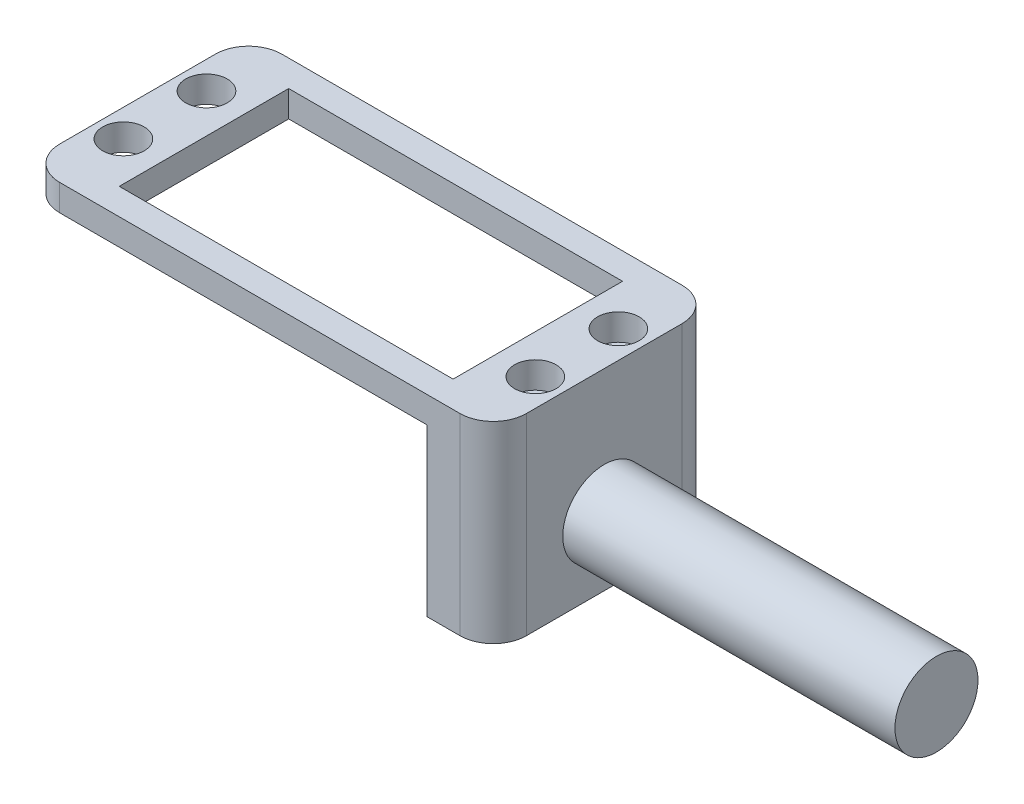
SolidWorks part; units mm, degrees
ref_plane "Front Plane" through (0, 0, 0) normal (0, 0, 1) x (1, 0, 0)
ref_plane "Top Plane" through (0, 0, 0) normal (0, 1, 0) x (1, 0, 0)
ref_plane "Right Plane" through (0, 0, 0) normal (1, 0, 0) x (0, 0, -1)
sketch "Sketch1" plane through (0, 0, 0) normal (0, 1, 0) x (1, 0, 0)
  line L0 (0, 13.375) -> (0, -13.375) construction
  line L1 (-20.1, 10.2) -> (20.1, 10.2)
  line L2 (-20.1, 10.2) -> (-20.1, -10.2)
  line L3 (-20.1, -10.2) -> (20.1, -10.2)
  line L4 (20.1, 10.2) -> (20.1, -10.2)
  line L5 (-20.1, 10.2) -> (20.1, -10.2) construction
  line L6 (-20.1, -10.2) -> (20.1, 10.2) construction
  line L7 (-28.1, 13.375) -> (28.1, 13.375)
  line L8 (-28.1, 13.375) -> (-28.1, -13.375)
  line L9 (-28.1, -13.375) -> (28.1, -13.375)
  line L10 (28.1, 13.375) -> (28.1, -13.375)
  line L11 (-28.1, 13.375) -> (28.1, -13.375) construction
  line L12 (-28.1, -13.375) -> (28.1, 13.375) construction
  circle A0 centre (24.8, 5) radius 2.5
  circle A1 centre (24.8, -5) radius 2.5
  circle A2 centre (-24.8, -5) radius 2.5
  circle A3 centre (-24.8, 5) radius 2.5
  point P0 (0, 0)
  point P6 (0, 0)
  point P17 (0, 0)
  dimension "D4" = 5
  dimension "D1" = 40.2
  dimension "D2" = 20.4
  dimension "D3" = 8
  dimension "D5" = 4.7
  dimension "D6" = 10
  dimension "D7" = 5.2
  dimension "D8" = 3.175
extrude "Boss-Extrude1" add sketch "Sketch1" along normal blind 3.175
sketch "Sketch3" plane through (0, 0, 0) normal (0, -1, 0) x (1, 0, 0)
  line L0 (-28.1, 13.375) -> (28.1, 13.375) construction
  line L1 (28.1, -13.375) -> (20.1, -13.375)
  line L2 (28.1, -13.375) -> (28.1, 13.375)
  line L3 (28.1, 13.375) -> (20.1, 13.375)
  line L4 (20.1, -13.375) -> (20.1, 13.375)
  line L5 (20.1, 10.2) -> (20.1, -10.2) construction
extrude "Boss-Extrude2" add sketch "Sketch3" along normal blind 20
fillet "Fillet1" radius 4 4 edges at (28.1, -8.4125, -13.375) (28.1, -8.4125, 13.375) (-28.1, 1.5875, 13.375) (-28.1, 1.5875, -13.375)
sketch "Sketch4" plane through (28.1, 0, 0) normal (1, 0, 0) x (0, 0, -1)
  line L0 (-9.375, 3.175) -> (9.375, 3.175) construction
  circle A0 centre (0, -11.825) radius 5
  dimension "D1" = 10
  dimension "D2" = 15
extrude "Boss-Extrude3" add sketch "Sketch4" along normal blind 40
